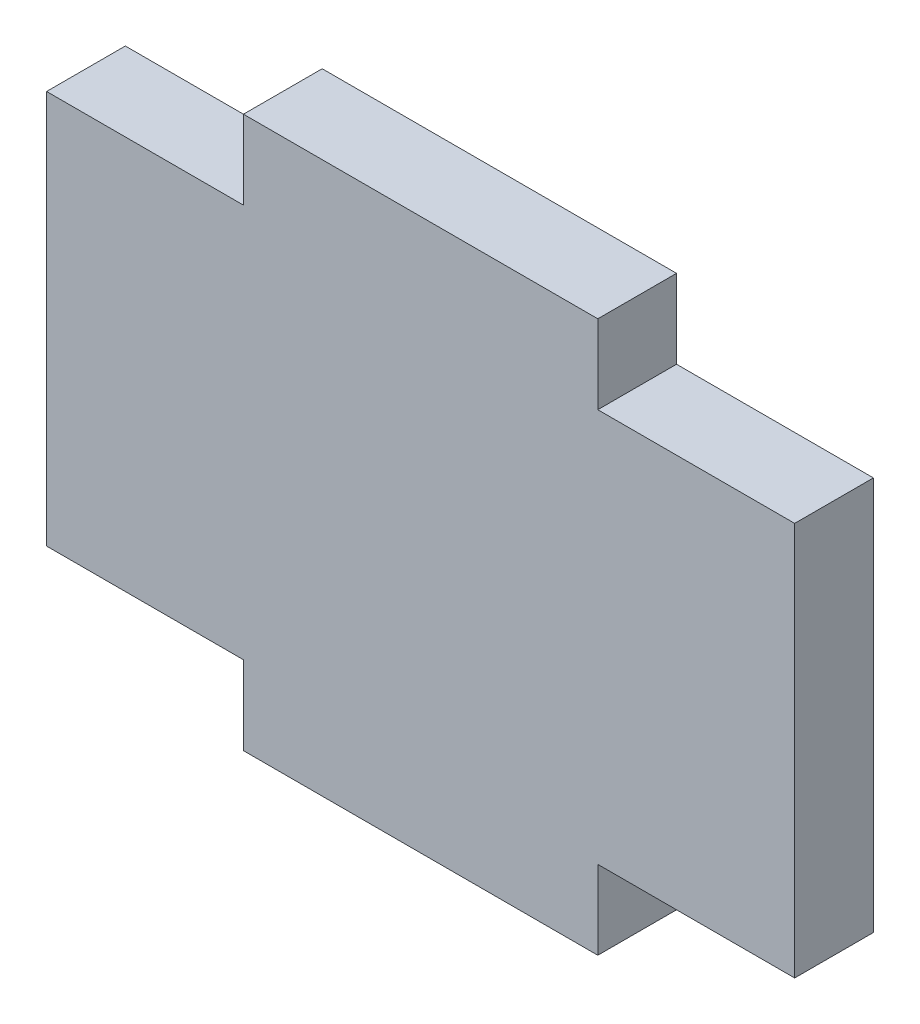
SolidWorks part; units mm, degrees
ref_plane "Front Plane" through (0, 0, 0) normal (0, 0, 1) x (1, 0, 0)
ref_plane "Top Plane" through (0, 0, 0) normal (0, 1, 0) x (1, 0, 0)
ref_plane "Right Plane" through (0, 0, 0) normal (1, 0, 0) x (0, 0, -1)
sketch "Sketch1" plane through (0, 0, 0) normal (0, 0, 1) x (1, 0, 0)
  line L0 (9, 0) -> (19, 0)
  line L1 (-19, 20) -> (-9, 20)
  line L2 (-19, 20) -> (-19, 0)
  line L3 (-19, 0) -> (-9, 0)
  line L4 (19, 20) -> (19, 0)
  line L5 (-19, 20) -> (19, 0) construction
  line L6 (0, 0) -> (0, 27.3651) construction
  line L7 (0, 10) -> (34.9577, 10) construction
  line L8 (-19, 0) -> (19, 20) construction
  line L9 (9, 20) -> (19, 20)
  line L10 (-9, 0) -> (-9, -4)
  line L11 (-9, -4) -> (9, -4)
  line L12 (9, 0) -> (9, -4)
  line L14 (-9, 20) -> (-9, 24)
  line L15 (-9, 24) -> (9, 24)
  line L16 (9, 20) -> (9, 24)
  dimension "D1" = 38
  dimension "D2" = 20
  dimension "D3" = 10
  dimension "D4" = 10
  dimension "D5" = 10
  dimension "D6" = 10
  dimension "D7" = 4
  dimension "D8" = 4
extrude "Boss-Extrude1" add sketch "Sketch1" along normal blind 4
